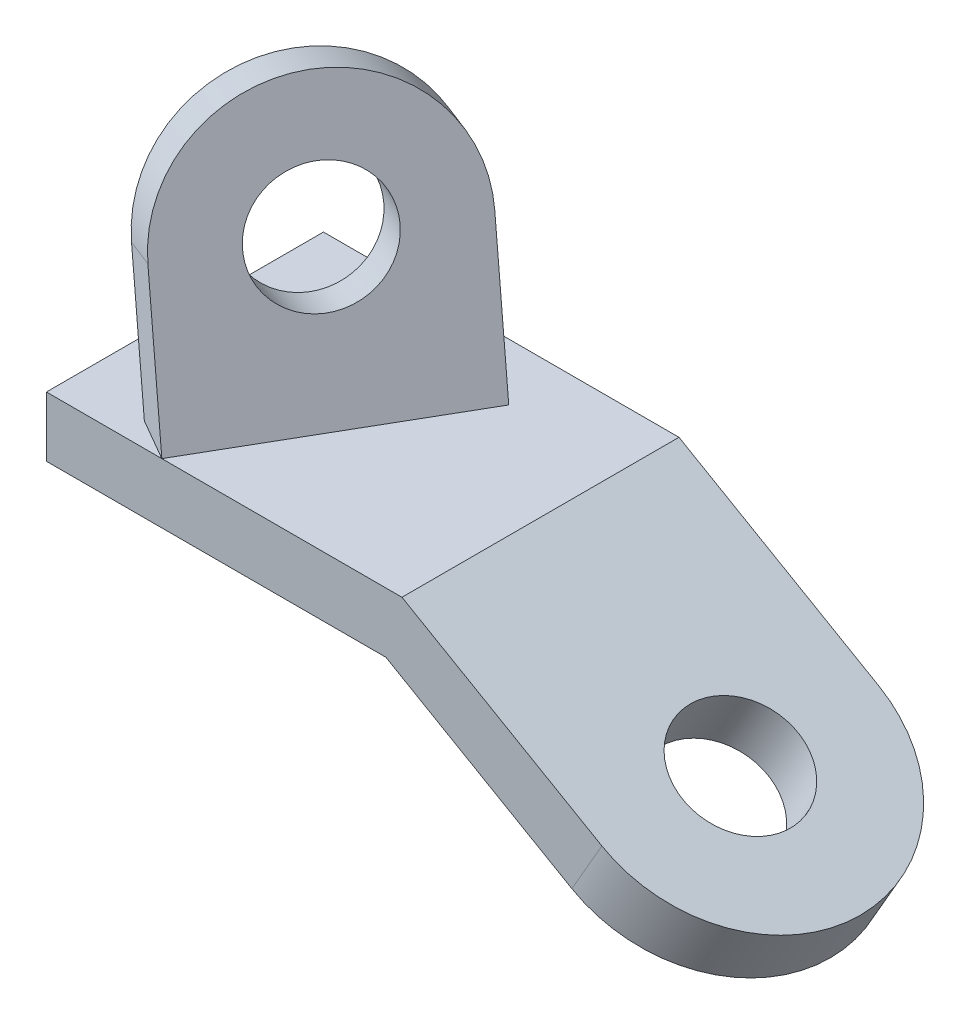
SolidWorks part; units mm, degrees
ref_plane "Front Plane" through (0, 0, 0) normal (0, 0, 1) x (1, 0, 0)
ref_plane "Top Plane" through (0, 0, 0) normal (0, 1, 0) x (1, 0, 0)
ref_plane "Right Plane" through (0, 0, 0) normal (1, 0, 0) x (0, 0, -1)
sketch "Sketch1" plane through (0, 0, 0) normal (0, 0, 1) x (1, 0, 0)
  line L1 (0, 0) -> (73.5167, 0)
  line L2 (0, 0) -> (0, 13)
  line L3 (0, 13) -> (77, 13)
  line L5 (77, 13) -> (146.282, -27)
  line L6 (73.5167, 0) -> (139.782, -38.2583)
  line L7 (146.282, -27) -> (139.782, -38.2583)
  point P4 (113.6998, 0)
  point P5 (139.2531, -37.9529)
  dimension "D1" = 13
  dimension "D2" = 13
  dimension "D3" = 150
  dimension "D4" = 77
  dimension "D5" = 80
extrude "Boss-Extrude1" add sketch "Sketch1" along normal mid plane 60
sketch "Sketch2" plane through (24.8792, 43.092, 0) normal (0.5, 0.866, 0) x (0.866, -0.5, 0)
  line L0 (140.184, 30) -> (60.184, 30) construction
  line L1 (140.184, -30) -> (140.184, 30) construction
  line L2 (140.184, -30) -> (60.184, -30) construction
  circle A0 centre (110.184, 0) radius 30
  circle A1 centre (110.184, 0) radius 12.5
  line M2 (140.184, 30) -> (60.184, 30)
  line M4 (60.184, -30) -> (140.184, -30)
  line M5 (140.184, -30) -> (140.184, 30)
  dimension "D1" = 25
extrude "Cut-Extrude1" cut sketch "Sketch2" against normal up to next contours A1 | A0 M5 M2 | A0 M4 M5
sketch "Sketch3" plane through (0, 13, 0) normal (0, 1, 0) x (1, 0, 0)
  line L0 (25, -30) -> (53.0729, 18.6236) construction
  line L1 (77, -30) -> (0, -30) construction
  line L2 (0, -30) -> (0, 30) construction
  point P6 (25, -30)
  dimension "D1" = 60
  dimension "D2" = 25
ref_plane "Plane1" through (32.4288, 10.0335, 18.7228) normal (0.8365, 0.2588, 0.483) x (0.5, 0, -0.866)
sketch "Sketch4" plane through (32.4288, 10.0335, 18.7228) normal (0.8365, 0.2588, 0.483) x (0.5, 0, -0.866)
  line L0 (41.5192, 35.0712) -> (41.5192, 3.0712)
  line L1 (41.5192, 3.0712) -> (-13.4808, 3.0712)
  line L2 (-13.4808, 3.0712) -> (-13.4808, 35.0712)
  line L5 (-13.4808, 3.0712) -> (42.665, 3.0712) construction
  circle A0 centre (14.0192, 35.0712) radius 12.5
  arc A1 (41.5192, 35.0712) -> (-13.4808, 35.0712) centre (14.0192, 35.0712) ccw
  point P10 (0, 0)
  dimension "D1" = 55
  dimension "D2" = 25
  dimension "D3" = 32
extrude "Boss-Extrude2" add sketch "Sketch4" against normal blind 10
